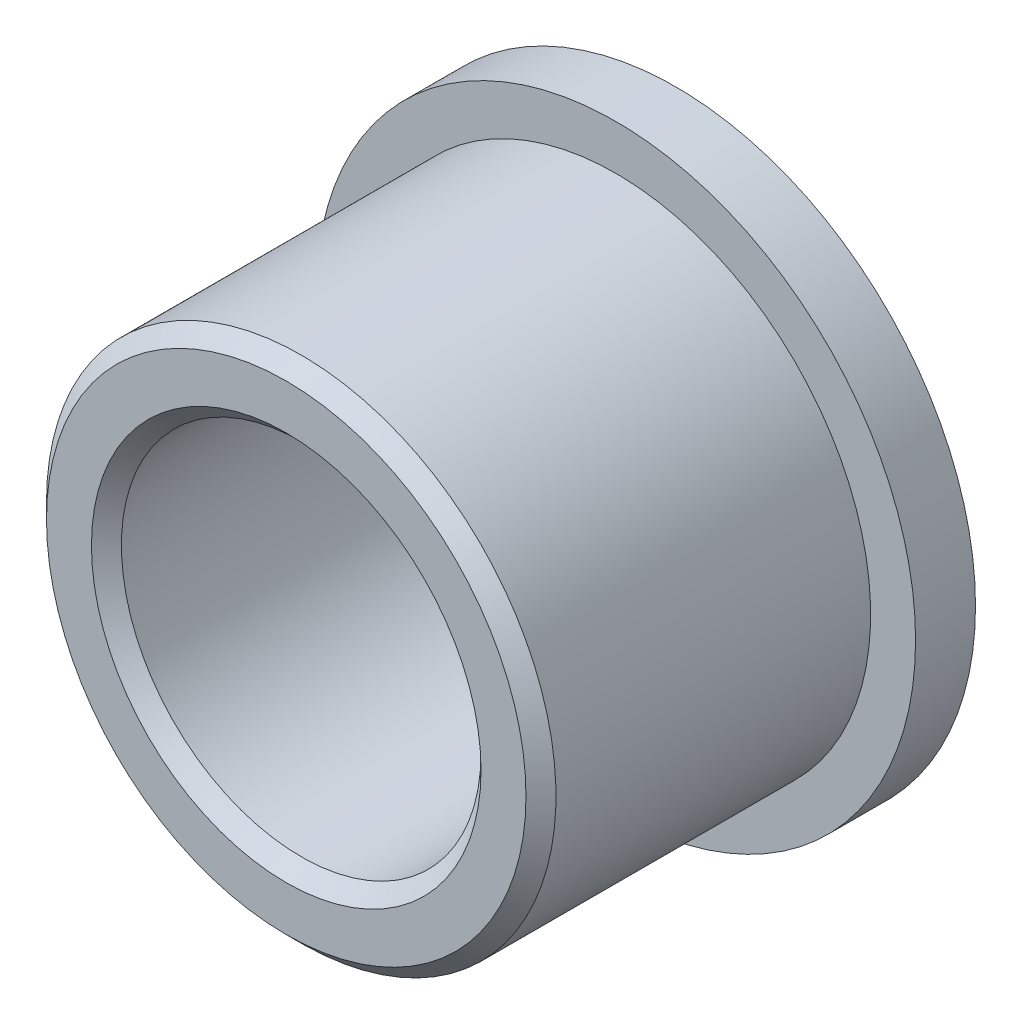
SolidWorks part; units mm, degrees
ref_plane "前视基准面" through (0, 0, 0) normal (0, 0, 1) x (1, 0, 0)
ref_plane "上视基准面" through (0, 0, 0) normal (0, 1, 0) x (1, 0, 0)
ref_plane "右视基准面" through (0, 0, 0) normal (1, 0, 0) x (0, 0, -1)
sketch "草图1" plane through (0, 0, 0) normal (0, 0, 1) x (1, 0, 0)
  circle A0 centre (0, 0) radius 10
  dimension "D1" = 20
extrude "凸台-拉伸1" add sketch "草图1" along normal blind 2
sketch "草图2" plane through (0, 0, 0) normal (0, 0, 1) x (1, 0, 0)
  circle A0 centre (0, 0) radius 8.5
  dimension "D1" = 17
extrude "凸台-拉伸2" add sketch "草图2" along normal blind 13
sketch "草图3" plane through (0, 0, 13) normal (0, 0, 1) x (1, 0, 0)
  circle A0 centre (0, 0) radius 6
  dimension "D1" = 12
extrude "切除-拉伸1" cut sketch "草图3" against normal through all
chamfer "倒角1" distance 0.5 angle 45 3 edges at (6, 0, 13) (6, 0, 0) (8.5, 0, 13)
